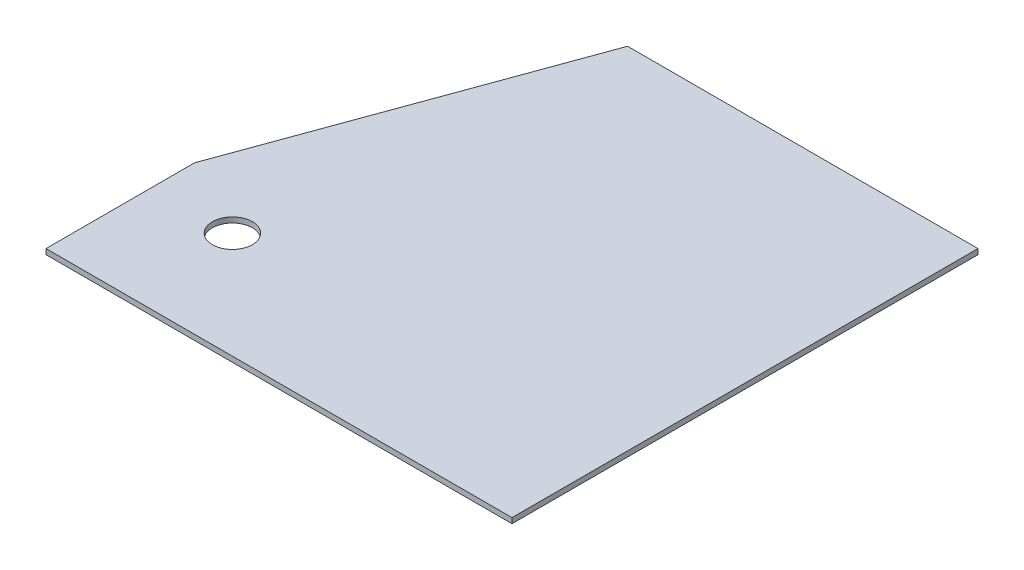
SolidWorks part; units mm, degrees
ref_plane "Front Plane" through (0, 0, 0) normal (0, 0, 1) x (1, 0, 0)
ref_plane "Top Plane" through (0, 0, 0) normal (0, 1, 0) x (1, 0, 0)
ref_plane "Right Plane" through (0, 0, 0) normal (1, 0, 0) x (0, 0, -1)
sketch "Sketch1" plane through (0, 0, 0) normal (0, 1, 0) x (1, 0, 0)
  line L0 (-175, 55.76) -> (-131.59, 175)
  line L5 (-175, 0) -> (0, 0)
  line L6 (-175, 0) -> (-175, 55.76)
  line L7 (-131.59, 175) -> (0, 175)
  line L8 (0, 0) -> (0, 175)
  point P6 (0, 0)
  dimension "D1" = 175
  dimension "D2" = 55.76
  dimension "D3" = 131.59
  dimension "D4" = 69.996
extrude "Boss-Extrude1" add sketch "Sketch1" along normal blind 2
sketch "Sketch2" plane through (0, 0, 0) normal (0, -1, 0) x (1, 0, 0)
  line L1 (-175, -55.76) -> (-175, 0) construction
  line L2 (-175, 0) -> (0, 0) construction
  circle A0 centre (-145, -40) radius 7.5
  dimension "D2" = 15
  dimension "D1" = 40
  dimension "D3" = 30
extrude "Cut-Extrude1" cut sketch "Sketch2" against normal blind 10
